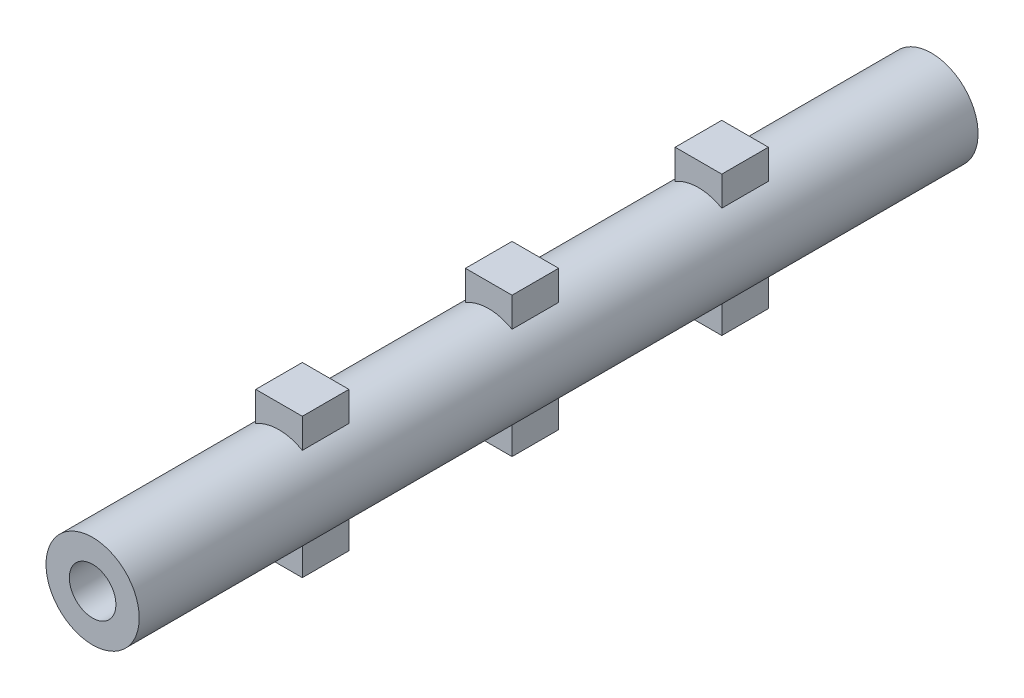
SolidWorks part; units mm, degrees
ref_plane "Front Plane" through (0, 0, 0) normal (0, 0, 1) x (1, 0, 0)
ref_plane "Top Plane" through (0, 0, 0) normal (0, 1, 0) x (1, 0, 0)
ref_plane "Right Plane" through (0, 0, 0) normal (1, 0, 0) x (0, 0, -1)
sketch "Sketch1" plane through (0, 0, 0) normal (0, 0, 1) x (1, 0, 0)
  circle A0 centre (0, 0) radius 5
  dimension "D1" = 10
extrude "Boss-Extrude1" add sketch "Sketch1" along normal blind 25
sketch "Sketch2" plane through (0, 0, 25) normal (0, 0, 1) x (1, 0, 0)
  line L1 (-2.5, -7.5) -> (2.5, -7.5)
  line L2 (-2.5, -7.5) -> (-2.5, 7.5)
  line L3 (-2.5, 7.5) -> (2.5, 7.5)
  line L4 (2.5, -7.5) -> (2.5, 7.5)
  line L5 (-2.5, -7.5) -> (2.5, 7.5) construction
  line L6 (-2.5, 7.5) -> (2.5, -7.5) construction
  point P0 (0, 0)
  dimension "D1" = 15
  dimension "D2" = 5
extrude "Boss-Extrude2" add sketch "Sketch2" against normal blind 5
sketch "Sketch3" plane through (0, 0, 0) normal (0, 0, -1) x (-1, 0, 0)
  line L1 (-2.5, -7.5) -> (2.5, -7.5)
  line L2 (-2.5, -7.5) -> (-2.5, 7.5)
  line L3 (-2.5, 7.5) -> (2.5, 7.5)
  line L4 (2.5, -7.5) -> (2.5, 7.5)
  line L5 (-2.5, -7.5) -> (2.5, 7.5) construction
  line L6 (-2.5, 7.5) -> (2.5, -7.5) construction
  point P0 (0, 0)
  dimension "D1" = 15
  dimension "D2" = 5
extrude "Boss-Extrude3" add sketch "Sketch3" against normal blind 2.5
sketch "Sketch5" plane through (0, 0, 0) normal (0, 0, -1) x (-1, 0, 0)
  line L0 (2.5, 4.3301) -> (2.5, 7.5) construction
  line L1 (-2.5, -7.5) -> (2.5, -7.5)
  line L2 (-2.5, -7.5) -> (-2.5, 7.5)
  line L3 (-2.5, 7.5) -> (2.5, 7.5)
  line L4 (2.5, -7.5) -> (2.5, 7.5)
  line L5 (-2.5, -7.5) -> (2.5, 7.5) construction
  line L6 (-2.5, 7.5) -> (2.5, -7.5) construction
  point P0 (0, 0)
extrude "Boss-Extrude5" add sketch "Sketch5" along normal blind 2.5
sketch "Sketch6" plane through (0, 0, 0) normal (0, 0, -1) x (-1, 0, 0)
  circle A0 centre (0, 0) radius 5
extrude "Boss-Extrude6" add sketch "Sketch6" along normal blind 25
sketch "Sketch7" plane through (0, 0, -25) normal (0, 0, -1) x (-1, 0, 0)
  line L1 (2.5, -7.5) -> (-2.5, -7.5)
  line L2 (2.5, -7.5) -> (2.5, 7.5)
  line L3 (2.5, 7.5) -> (-2.5, 7.5)
  line L4 (-2.5, -7.5) -> (-2.5, 7.5)
  line L5 (2.5, -7.5) -> (-2.5, 7.5) construction
  line L6 (2.5, 7.5) -> (-2.5, -7.5) construction
  point P0 (0, 0)
  dimension "D1" = 15
  dimension "D2" = 5
extrude "Boss-Extrude7" add sketch "Sketch7" against normal blind 5
hole_wizard "Ø5.0mm Dowel Hole1" positions "Sketch11" profile "Sketch12" hole size "Ø5.0" standard "ANSI Metric" end condition through all
sketch "Sketch11" plane through (0, 0, 25) normal (0, 0, 1) x (1, 0, 0)
  point P0 (0, 0)
sketch "Sketch12" plane through (0, 0, 25) normal (1, 0, 0) x (0, -1, 0)
  line L0 (0, 0) -> (0, 50)
  line L1 (0, 50) -> (2.5, 50)
  line L2 (2.5, 50) -> (2.5, 0)
  line L5 (2.5, 0) -> (0, 0)
  line L11 (0, -6.35) -> (0, 107.95) construction
  dimension "Thru Hole Dia." = 5
  dimension "Thru Hole Depth" = 50
sketch "Sketch14" plane through (0, 0, -25) normal (0, 0, -1) x (-1, 0, 0)
  circle A0 centre (0, 0) radius 5
extrude "Boss-Extrude8" add sketch "Sketch14" along normal blind 20
sketch "Sketch15" plane through (0, 0, 25) normal (0, 0, 1) x (1, 0, 0)
  circle A0 centre (0, 0) radius 5
extrude "Boss-Extrude9" add sketch "Sketch15" along normal blind 20
hole_wizard "Ø5.0mm Dowel Hole2" positions "Sketch16" profile "Sketch17" hole size "Ø5.0" standard "ANSI Metric" end condition through all
sketch "Sketch16" plane through (0, 0, -45) normal (0, 0, -1) x (-1, 0, 0)
  point P0 (0, 0)
sketch "Sketch17" plane through (0, 0, -45) normal (1, 0, 0) x (0, 1, 0)
  line L0 (0, 0) -> (0, 90)
  line L1 (0, 90) -> (2.5, 90)
  line L2 (2.5, 90) -> (2.5, 0)
  line L5 (2.5, 0) -> (0, 0)
  line L11 (0, -6.35) -> (0, 107.95) construction
  dimension "Thru Hole Dia." = 5
  dimension "Thru Hole Depth" = 90
